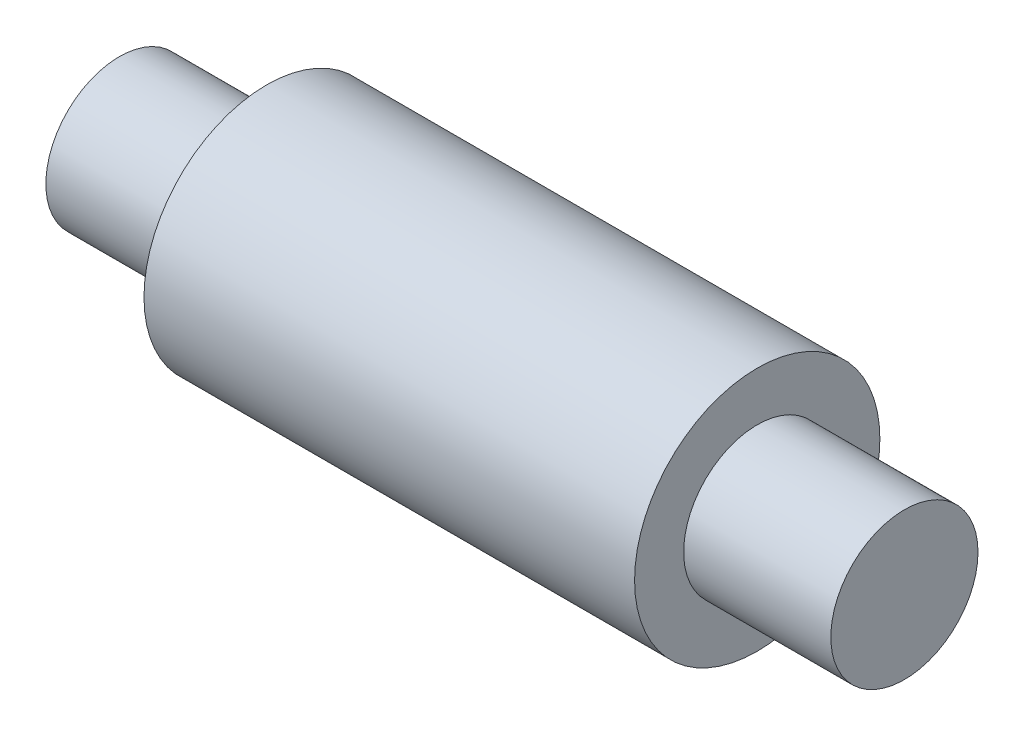
SolidWorks part; units mm, degrees
ref_plane "Front Plane" through (0, 0, 0) normal (0, 0, 1) x (1, 0, 0)
ref_plane "Top Plane" through (0, 0, 0) normal (0, 1, 0) x (1, 0, 0)
ref_plane "Right Plane" through (0, 0, 0) normal (1, 0, 0) x (0, 0, -1)
sketch "Sketch1" plane through (0, 0, 0) normal (1, 0, 0) x (0, 0, -1)
  circle A0 centre (0, 0) radius 63.5
  dimension "D1" = 127
extrude "Boss-Extrude1" add sketch "Sketch1" along normal mid plane 254
sketch "Sketch3" plane through (0, 0, 0) normal (1, 0, 0) x (0, 0, -1)
  circle A0 centre (0, 0) radius 38.1
  dimension "D1" = 76.2
extrude "Boss-Extrude2" add sketch "Sketch3" along normal mid plane 406.4
